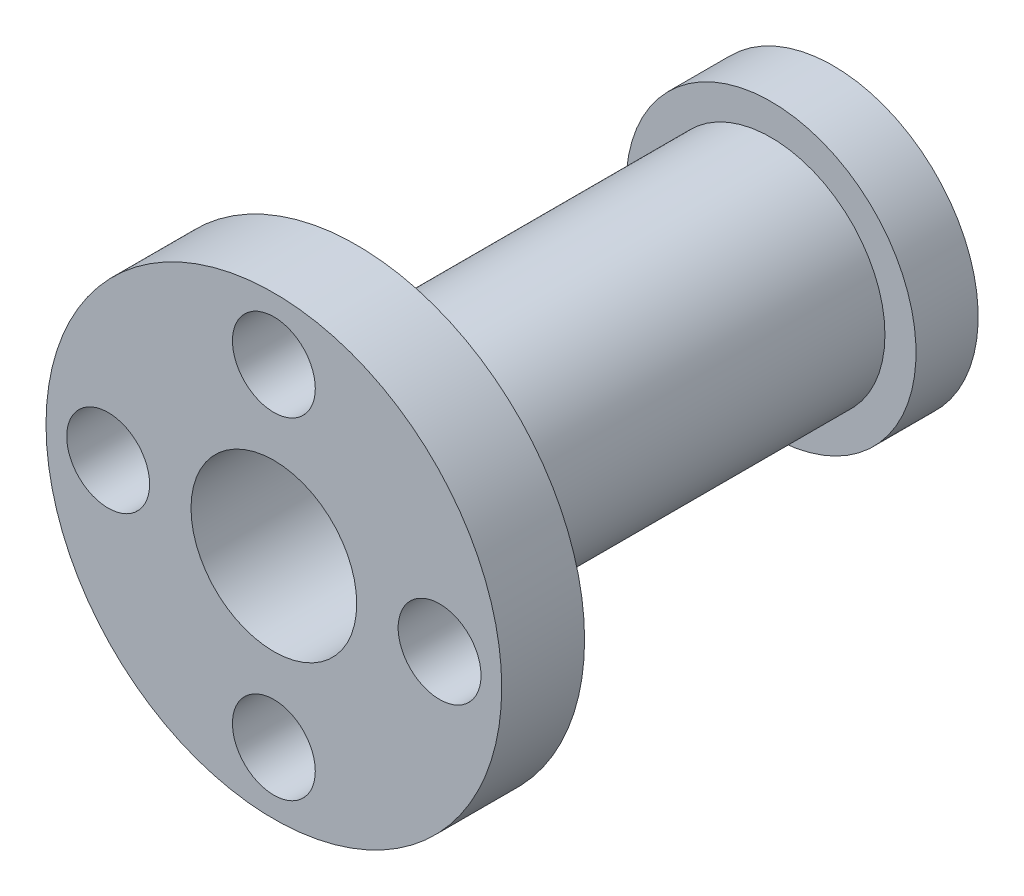
SolidWorks part; units mm, degrees
ref_plane "前视基准面" through (0, 0, 0) normal (0, 0, 1) x (1, 0, 0)
ref_plane "上视基准面" through (0, 0, 0) normal (0, 1, 0) x (1, 0, 0)
ref_plane "右视基准面" through (0, 0, 0) normal (1, 0, 0) x (0, 0, -1)
sketch "草图1" plane through (0, 0, 0) normal (0, 0, 1) x (1, 0, 0)
  circle A0 centre (0, 0) radius 11
  circle A1 centre (0, 0) radius 8 construction
  circle A2 centre (0, 8) radius 2
  circle A3 centre (0, 0) radius 8 construction
  circle A4 centre (8, 0) radius 2
  circle A5 centre (0, 0) radius 8 construction
  circle A6 centre (0, -8) radius 2
  circle A7 centre (0, 0) radius 8 construction
  circle A8 centre (-8, 0) radius 2
  circle A9 centre (0, 0) radius 4
  point P18 (0, 0)
  dimension "D1" = 22
  dimension "D2" = 16
  dimension "D3" = 4
  dimension "D4" = 4
  dimension "D5" = 8
extrude "凸台-拉伸1" add sketch "草图1" along normal blind 4
sketch "草图2" plane through (0, 0, 0) normal (0, 0, -1) x (-1, 0, 0)
  circle A0 centre (0, 0) radius 4
  circle A1 centre (0, 0) radius 5.5
  dimension "D1" = 11
extrude "凸台-拉伸2" add sketch "草图2" along normal blind 20
sketch "草图3" plane through (0, 0, -20) normal (0, 0, -1) x (-1, 0, 0)
  circle A0 centre (0, 0) radius 4
  circle A1 centre (0, 0) radius 7
  dimension "D1" = 14
extrude "凸台-拉伸3" add sketch "草图3" along normal blind 3
